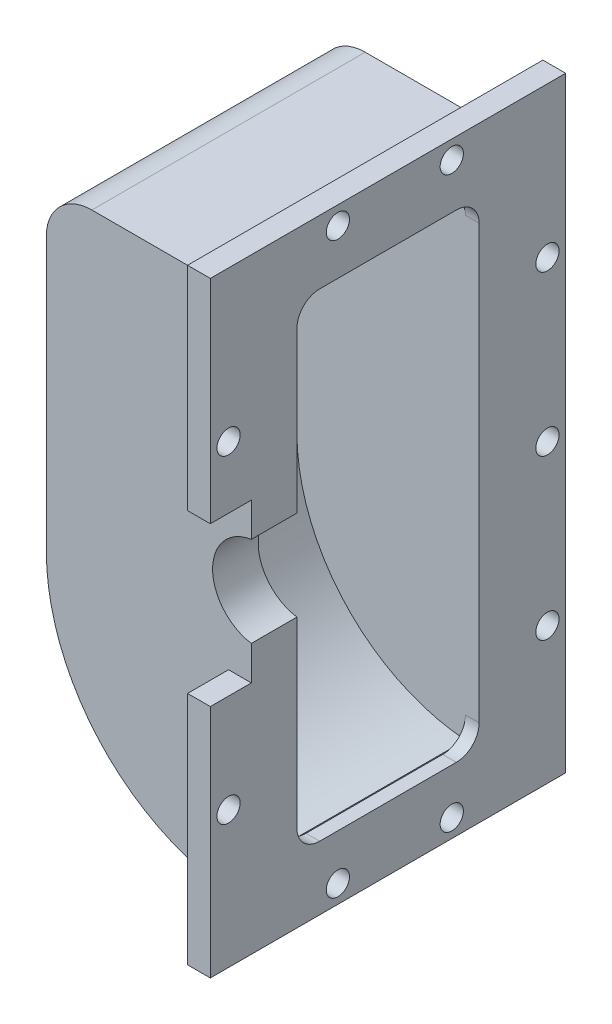
SolidWorks part; units mm, degrees
ref_plane "Front Plane" through (0, 0, 0) normal (0, 0, 1) x (1, 0, 0)
ref_plane "Top Plane" through (0, 0, 0) normal (0, 1, 0) x (1, 0, 0)
ref_plane "Right Plane" through (0, 0, 0) normal (1, 0, 0) x (0, 0, -1)
sketch "Sketch2" plane through (0, 0, 0) normal (0, 0, 1) x (1, 0, 0)
  line L0 (0, 0) -> (-10, 0)
  line L1 (-10, 0) -> (-10, -18)
  line L2 (-10, -18) -> (-70, -18)
  line L3 (-90, -38) -> (-90, -157.7737)
  line L5 (0, -266) -> (0, -147.7737)
  line L7 (-10, -247.2164) -> (-10, -266)
  line L8 (-10, -266) -> (0, -266)
  line L9 (3, -40.2128) -> (3, -128) construction
  line L10 (30.8088, -128) -> (3, -128) construction
  line L11 (0, -108.2263) -> (0, 0)
  line L12 (0, -157.7737) -> (29.0848, -157.7737) construction
  line L13 (0, -28) -> (-60, -28)
  line L14 (-80, -48) -> (-80, -157.7737)
  line L15 (0, -108.2263) -> (0, -147.7737)
  arc A1 (-90, -157.7737) -> (-10, -247.2164) centre (0, -157.7737) ccw
  arc A2 (3, -67.8237) -> (0, -67.7737) centre (0, -157.7737) ccw
  arc A3 (-90, -38) -> (-70, -18) centre (-70, -38) cw
  arc A4 (-80, -48) -> (-60, -28) centre (-60, -48) cw
  arc A5 (3, -77.83) -> (0, -77.7737) centre (0, -157.7737) ccw
  arc A6 (-80, -157.7737) -> (0, -237.7737) centre (0, -157.7737) ccw
  dimension "D10" = 180
  dimension "D4" = 20
  dimension "D12" = 20
  dimension "D14" = 160
  dimension "D1" = 10
  dimension "D2" = 266
  dimension "D3" = 18
  dimension "D5" = 90
  dimension "D6" = 3
  dimension "D7" = 138
  dimension "D9" = 10
  dimension "D11" = 28
  dimension "D13" = 10
extrude "Boss-Extrude2" add sketch "Sketch2" along normal blind 120 contours L14 A6 L5 L15 L11 L13 A4 | A6 L14 A4 L13 L11 L0 L1 L2 A3 L3 A1 L7 L8 L5
sketch "Sketch3" plane through (0, 0, 120) normal (0, 0, 1) x (1, 0, 0)
  line L0 (0, 0) -> (0, -128) construction
  line L1 (3, -74.9067) -> (3, -128) construction
  line L2 (44.7273, -128) -> (0, -128) construction
  line L3 (-10, -266) -> (0, -266) construction
  line L4 (0, -128) -> (0, -266) construction
  arc A0 (0, -108.2263) -> (0, -147.7737) centre (3, -128) ccw
  line M7 (0, -266) -> (0, 0)
  dimension "D3" = 40
  dimension "D1" = 138
  dimension "D2" = 3
extrude "Cut-Extrude1" cut sketch "Sketch3" against normal blind 18 and the other way blind 10 contours A0 M7
sketch "Sketch5" plane through (-10, 0, 0) normal (-1, 0, 0) x (0, 0, 1)
  line L0 (0, -266) -> (-18, -266)
  line L1 (-18, -266) -> (-18, 0)
  line L2 (-18, 0) -> (138, 0)
  line L3 (138, 0) -> (138, -266)
  line L4 (138, -266) -> (120, -266)
  line L5 (0, -38) -> (0, -157.7737) construction
  line L6 (120, -38) -> (120, -157.7737) construction
  line L12 (0, -247.2164) -> (0, -266)
  line L13 (0, -266) -> (120, -266)
  line L14 (120, -266) -> (120, -247.2164)
  line L15 (120, -247.2164) -> (0, -247.2164)
  line L17 (0, -266) -> (120, -266)
  dimension "D1" = 18
  dimension "D2" = 18
  dimension "D3" = 0
extrude "Boss-Extrude3" add sketch "Sketch5" against normal blind 10
hole_wizard "Ø1.0mm Dowel Hole1" positions "Sketch6" profile "Sketch7" hole size "Ø1.0" standard "ISO" end condition through all
sketch "Sketch6" plane through (-10, 0, 0) normal (-1, 0, 0) x (0, 0, 1)
  line L0 (138, 0) -> (-18, 0) construction
  line L1 (-18, 0) -> (-18, -266) construction
  line L2 (-10, -66) -> (-10, -206) construction
  line L4 (138, -266) -> (-18, -266) construction
  line L5 (32, -258) -> (82, -258) construction
  line L7 (130, -66) -> (130, -206) construction
  line L9 (138, -266) -> (138, 0) construction
  point P0 (32, -8)
  point P2 (82, -8)
  point P4 (-10, -66)
  point P6 (-10, -136)
  point P8 (-10, -206)
  point P10 (32, -258)
  point P12 (82, -258)
  point P14 (130, -206)
  point P16 (130, -66)
  dimension "D1" = 8
  dimension "D2" = 8
  dimension "D3" = 50
  dimension "D4" = 50
  dimension "D5" = 8
  dimension "D6" = 200
  dimension "D7" = 8
  dimension "D8" = 130
  dimension "D9" = 60
  dimension "D10" = 50
  dimension "D11" = 8
  dimension "D12" = 50
  dimension "D13" = 8
  dimension "D14" = 60
  dimension "D15" = 200
sketch "Sketch7" plane through (-10, -8, 32) normal (0, 1, 0) x (0, 0, 1)
  line L0 (0, 0) -> (0, 10)
  line L1 (0, 10) -> (5.1, 10)
  line L2 (5.1, 10) -> (5.1, 0)
  line L5 (5.1, 0) -> (0, 0)
  line L11 (0, -6.35) -> (0, 107.95) construction
  dimension "Thru Hole Dia." = 10.2
  dimension "Thru Hole Depth" = 10
sketch "Sketch8" plane through (-10, 0, 0) normal (-1, 0, 0) x (0, 0, 1)
  line L0 (138, -93.3) -> (120, -93.3)
  line L1 (138, -266) -> (138, 0) construction
  line L2 (120, -38) -> (120, -157.7737) construction
  line L3 (120, -93.3) -> (120, -162.8)
  line L4 (120, -162.8) -> (138, -162.8)
  line L5 (138, -266) -> (-18, -266) construction
  line L6 (138, -93.3) -> (138, -162.8)
  dimension "D1" = 69.5
  dimension "D2" = 103.2
extrude "Cut-Extrude2" cut sketch "Sketch8" against normal blind 10
sketch "Sketch9" plane through (0, 0, 120) normal (0, 0, 1) x (1, 0, 0)
  line L0 (0, -129.8766) -> (0, -162.8) construction
  line L1 (3, -104.876) -> (3, -128) construction
  line L2 (36.6309, -128) -> (0, -128) construction
  line L4 (0, -266) -> (-10, -266) construction
  line L5 (0, -93.3) -> (0, -162.8)
  arc A0 (0, -108.2263) -> (0, -147.7737) centre (3, -128) ccw
  line M12 (-10, -112.8013) -> (-10, -143.1987)
  arc M13 (-10, -143.1987) -> (-10, -112.8013) centre (3, -128) cw
  dimension "D3" = 40
  dimension "D1" = 3
  dimension "D2" = 138
extrude "Cut-Extrude3" cut sketch "Sketch9" against normal blind 20 contours L5 A0 M12 | M13 M12
sketch "Sketch10" plane through (0, 0, 0) normal (1, 0, 0) x (0, 0, -1)
  line L0 (18, 0) -> (18, -266) construction
  line L1 (-30, -238) -> (-90, -238)
  line L2 (-20, -228) -> (-20, -38)
  line L3 (-30, -28) -> (-90, -28)
  line L4 (-100, -228) -> (-100, -38)
  line L5 (-138, -266) -> (-138, -162.8) construction
  line L6 (-138, -266) -> (18, -266) construction
  line L7 (-138, 0) -> (18, 0) construction
  arc A0 (-30, -238) -> (-20, -228) centre (-30, -228) ccw
  arc A1 (-90, -238) -> (-100, -228) centre (-90, -228) cw
  arc A2 (-30, -28) -> (-20, -38) centre (-30, -38) cw
  arc A3 (-100, -38) -> (-90, -28) centre (-90, -38) cw
  dimension "D5" = 10
  dimension "D1" = 38
  dimension "D2" = 38
  dimension "D3" = 28
  dimension "D4" = 28
ref_plane "Plane1" through (0, 0, 20) normal (0, 0, -1) x (-1, 0, 0)
sketch "Sketch12" plane through (0, 0, 20) normal (0, 0, -1) x (-1, 0, 0)
  line L0 (0, -28) -> (60, -28)
  line L1 (0, -28) -> (0, -38) construction
  line L2 (80, -48) -> (80, -157.7737)
  line L3 (6, -28) -> (6, -237.5484)
  line L4 (0, -228) -> (0, -38) construction
  line L7 (90, -38) -> (90, -157.7737) construction
  line L12 (-9.2127, -157.7737) -> (0, -157.7737) construction
  arc A1 (6, -237.5484) -> (80, -157.7737) centre (0, -157.7737) ccw
  arc A2 (80, -48) -> (60, -28) centre (60, -48) ccw
  dimension "D6" = 160
  dimension "D2" = 20
  dimension "D1" = 10
  dimension "D3" = 6
extrude "Cut-Extrude4" cut sketch "Sketch12" against normal blind 80
extrude "Cut-Extrude5" cut sketch "Sketch10" against normal blind 6
